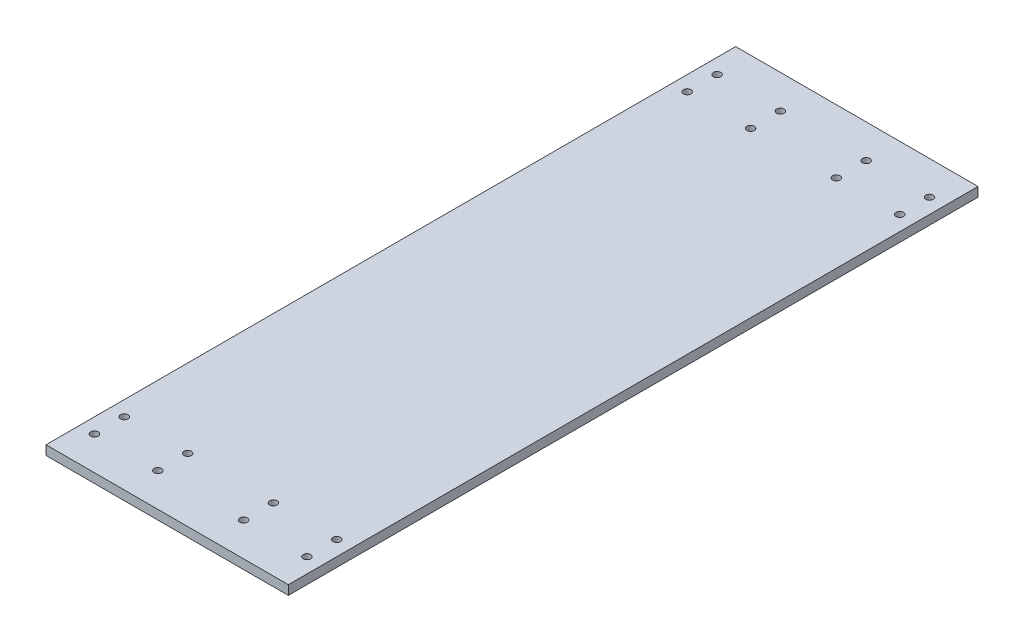
SolidWorks part; units mm, degrees
material "Pine"
ref_plane "Front Plane" through (0, 0, 0) normal (0, 0, 1) x (1, 0, 0)
ref_plane "Top Plane" through (0, 0, 0) normal (0, 1, 0) x (1, 0, 0)
ref_plane "Right Plane" through (0, 0, 0) normal (1, 0, 0) x (0, 0, -1)
sketch "Sketch2" plane through (0, 0, 0) normal (0, 1, 0) x (1, 0, 0)
  line L1 (-65, -185) -> (65, -185)
  line L2 (-65, -185) -> (-65, 185)
  line L3 (-65, 185) -> (65, 185)
  line L4 (65, -185) -> (65, 185)
  line L5 (-65, -185) -> (65, 185) construction
  line L6 (-65, 185) -> (65, -185) construction
  point P0 (0, 0)
  dimension "D1" = 370
  dimension "D2" = 130
extrude "Boss-Extrude1" add sketch "Sketch2" along normal blind 5
sketch "Sketch3" plane through (0, 5, 0) normal (0, 1, 0) x (1, 0, 0)
  line L0 (-65, 185) -> (-65, -185) construction
  line L1 (65, 185) -> (-65, 185) construction
  circle A0 centre (-57, 167) radius 2
  circle A1 centre (-57, 151) radius 2
  circle A2 centre (-23, 167) radius 2
  circle A3 centre (-23, 151) radius 2
  dimension "D1" = 4
  dimension "D2" = 4
  dimension "D3" = 4
  dimension "D4" = 4
  dimension "D5" = 8
  dimension "D6" = 34
  dimension "D7" = 18
  dimension "D8" = 16
extrude "Cut-Extrude1" cut sketch "Sketch3" against normal blind 10
mirror "Mirror1" about plane through (0, 0, 0) normal (0, 0, 1) of "Cut-Extrude1" second plane through (0, 0, 0) second plane normal (1, 0, 0)
